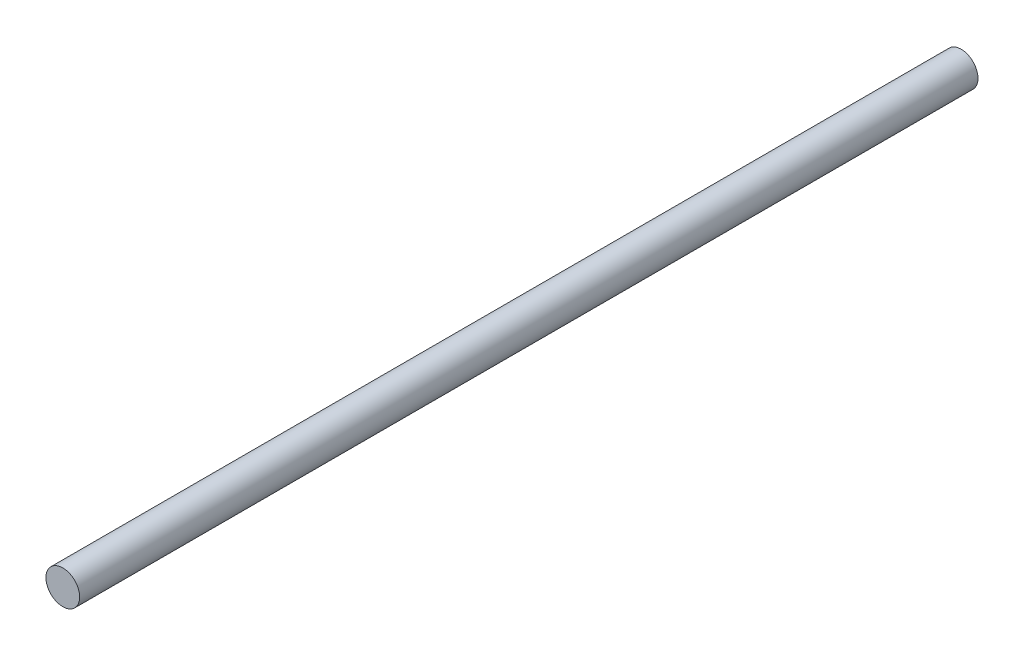
SolidWorks part; units mm, degrees
ref_plane "Front Plane" through (0, 0, 0) normal (0, 0, 1) x (1, 0, 0)
ref_plane "Top Plane" through (0, 0, 0) normal (0, 1, 0) x (1, 0, 0)
ref_plane "Right Plane" through (0, 0, 0) normal (1, 0, 0) x (0, 0, -1)
sketch "Sketch1" plane through (0, 0, 0) normal (0, 0, 1) x (1, 0, 0)
  circle A0 centre (0, 0) radius 15
  dimension "D1" = 30
extrude "Boss-Extrude1" add sketch "Sketch1" along normal blind 800
